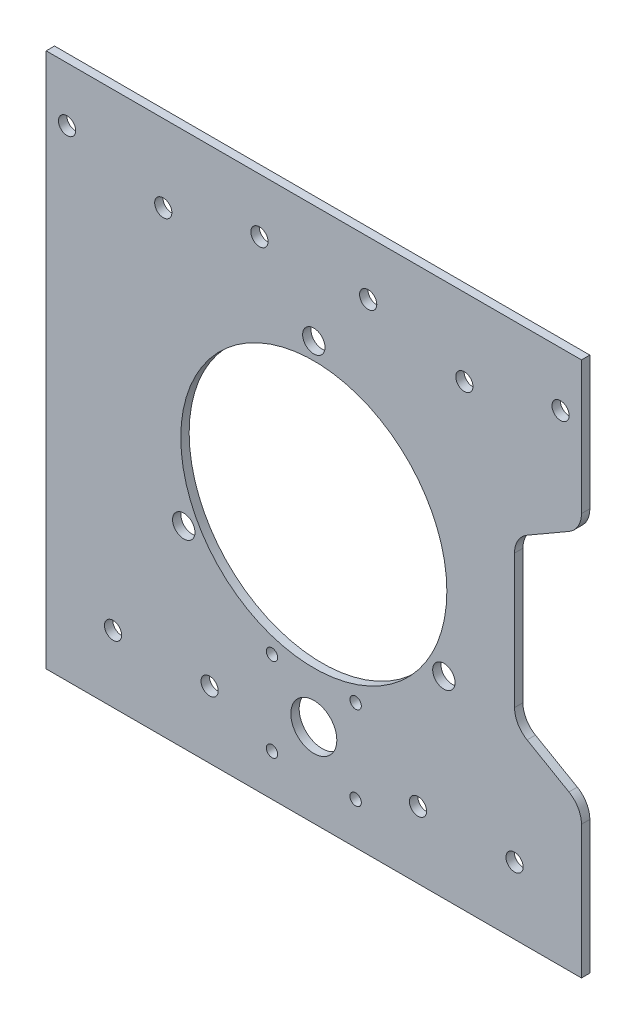
SolidWorks part; units mm, degrees
ref_plane "Front Plane" through (0, 0, 0) normal (0, 0, 1) x (1, 0, 0)
ref_plane "Top Plane" through (0, 0, 0) normal (0, 1, 0) x (1, 0, 0)
ref_plane "Right Plane" through (0, 0, 0) normal (1, 0, 0) x (0, 0, -1)
sketch "Sketch1" plane through (0, 0, 0) normal (0, 0, 1) x (1, 0, 0)
  line L1 (-101.6, -101.6) -> (101.6, -101.6)
  line L2 (-101.6, -101.6) -> (-101.6, 101.6)
  line L3 (-101.6, 101.6) -> (101.6, 101.6)
  line L4 (101.6, -101.6) -> (101.6, 101.6)
  line L5 (-101.6, -101.6) -> (101.6, 101.6) construction
  line L6 (-101.6, 101.6) -> (101.6, -101.6) construction
  point P0 (0, 0)
  dimension "D1" = 203.2
  dimension "D2" = 203.2
extrude "Boss-Extrude1" add sketch "Sketch1" against normal blind 3.175
sketch "Sketch4" plane through (0, 0, 0) normal (1, 0, 0) x (0, 0, -1)
  line L0 (0, 101.6) -> (0, -101.6) construction
  line L1 (0, 63.5) -> (-1.9844, 63.5)
  line L2 (0, 63.5) -> (0, 101.6)
  line L3 (0, 101.6) -> (-0.4801, 103.5254) construction
  line L4 (-1.9844, 63.5) -> (-1.9844, 101.6)
  line L5 (36.9683, 110.8172) -> (0, 101.6)
  line L6 (36.9683, 110.8172) -> (36.4882, 112.7427)
  line L7 (0, 101.6) -> (-1.9844, 101.6) construction
  line L8 (36.4882, 112.7427) -> (-0.4801, 103.5254)
  arc A0 (-0.4801, 103.5254) -> (-1.9844, 101.6) centre (-5.5035, 105.8998) ccw
  circle A1 centre (-5.5035, 105.8998) radius 3.7507
  dimension "D4" = 5.5562
  dimension "D1" = 1.9844
  dimension "D2" = 104
  dimension "D3" = 38.1
  dimension "D6" = 38.1
extrude "Boss-Extrude2" [suppressed] add sketch "Sketch4" along normal mid plane 203.2 separate body
sketch "Sketch5" [suppressed] plane through (0, 0, 1.9844) normal (0, 0, 1) x (1, 0, 0)
  line L0 (101.6, 63.5) -> (-101.6, 63.5) construction
  line L1 (-12.7, 63.5) -> (12.7, 63.5)
  line L2 (-12.7, 63.5) -> (-12.7, 116.2378)
  line L3 (-12.7, 116.2378) -> (12.7, 116.2378)
  line L4 (12.7, 63.5) -> (12.7, 116.2378)
  line L5 (-101.6, 101.6) -> (-101.6, 63.5) construction
  line L6 (101.6, 101.6) -> (101.6, 63.5) construction
  line L7 (-93.6625, 80.9625) -> (-101.6, 80.9625) construction
  line L8 (-93.6625, 80.9625) -> (-20.6375, 80.9625) construction
  line L9 (101.6, 101.6) -> (-101.6, 101.6) construction
  line L11 (0, 101.6) -> (0, 63.5) construction
  line L12 (-20.6375, 80.9625) -> (-12.7, 80.9625) construction
  line L13 (-57.15, 80.9625) -> (-57.15, 72.2313) construction
  line L14 (-57.15, 72.2313) -> (-57.15, 63.5) construction
  circle A0 centre (-93.6625, 80.9625) radius 4.3656
  circle A1 centre (-20.6375, 80.9625) radius 4.3656
  circle A2 centre (20.6375, 80.9625) radius 4.3656
  circle A3 centre (93.6625, 80.9625) radius 4.3656
  circle A4 centre (-57.15, 72.2313) radius 4.3656
  circle A5 centre (57.15, 72.2312) radius 4.3656
  dimension "D5" = 8.7312
  dimension "D3" = 8.7312
  dimension "D1" = 88.9
  dimension "D2" = 88.9
  dimension "D4" = 17.4625
  dimension "D6" = 7.9375
extrude "Cut-Extrude1" [suppressed] cut sketch "Sketch5" against normal through all both and the other way through all
sketch "Sketch6" [suppressed] plane through (0, 97.5792, 24.3292) normal (0, 0.9703, 0.2419) x (1, 0, 0)
  line L0 (101.6, 62.6793) -> (12.7, 62.6793) construction
  line L1 (12.7, 62.6793) -> (12.7, 24.5793) construction
  line L2 (-12.7, 24.5793) -> (-12.7, 62.6793) construction
  line B0 (93.6625, 45.2168) -> (101.6, 45.2168) construction
  line B1 (93.6625, 45.2168) -> (20.6375, 45.2168) construction
  line B2 (20.6375, 45.2168) -> (12.7, 45.2168) construction
  line B3 (57.15, 45.2168) -> (57.15, 53.948) construction
  line B4 (57.15, 53.948) -> (57.15, 62.6793) construction
  circle B5 centre (93.6625, 45.2168) radius 4.3656
  circle B6 centre (20.6375, 45.2168) radius 4.3656
  circle B7 centre (57.15, 53.948) radius 4.3656
  circle B8 centre (-20.6375, 43.6293) radius 4.3656
  circle B9 centre (-93.6625, 43.6293) radius 4.3656
  circle B10 centre (-57.15, 52.3605) radius 4.3656
sketch_block_instance "Block2-1"
sketch_block "Block2" parameters "D1"=8.7312
sketch_block_instance "Block2-2"
extrude "Cut-Extrude2" [suppressed] cut sketch "Sketch6" against normal through all
sketch "Sketch8" plane through (0, 0, 0) normal (0, 0, 1) x (1, 0, 0)
  line L0 (0, 0) -> (0, 57) construction
  line L1 (-49.3634, -28.5) -> (0, 0) construction
  line L2 (49.3634, -28.5) -> (0, 0) construction
  circle A0 centre (0, 0) radius 50.5
  circle A1 centre (0, 0) radius 57 construction
  circle A2 centre (0, 57) radius 4.25
  circle A3 centre (-49.3634, -28.5) radius 4.25
  circle A4 centre (49.3634, -28.5) radius 4.25
  dimension "D1" = 101
  dimension "D4" = 114
  dimension "D5" = 8.5
  dimension "D2" = 120
  dimension "D3" = 120
extrude "Cut-Extrude3" cut sketch "Sketch8" against normal through all
sketch "Sketch10" plane through (0, 0, 0) normal (0, 0, 1) x (1, 0, 0)
  line L0 (101.6, -101.6) -> (101.6, -51.0632) construction
  line L1 (101.6, -101.6) -> (101.6, 101.6) construction
  line L2 (96.8375, 42.8143) -> (80.9625, 33.6489)
  line L3 (76.2, 25.4) -> (76.2, -25.4)
  line L4 (80.9625, -33.6489) -> (96.8375, -42.8143)
  line L5 (101.6, 51.0632) -> (101.6, 101.6) construction
  line L6 (101.6, -51.0632) -> (101.6, 51.0632)
  arc A0 (76.2, -25.4) -> (80.9625, -33.6489) centre (85.725, -25.4) ccw
  arc A1 (80.9625, 33.6489) -> (76.2, 25.4) centre (85.725, 25.4) ccw
  arc A2 (101.6, 51.0632) -> (96.8375, 42.8143) centre (92.075, 51.0632) cw
  arc A3 (96.8375, -42.8143) -> (101.6, -51.0632) centre (92.075, -51.0632) cw
  dimension "D1" = 9.525
  dimension "D2" = 50.8
  dimension "D3" = 25.4
  dimension "D4" = 120
  dimension "D5" = 120
extrude "Cut-Extrude4" cut sketch "Sketch10" against normal through all
hole_wizard "1/4 Clearance Hole2" positions "Sketch12" profile "Sketch11" hole size "1/4" standard "ANSI Inch" end condition through all
sketch "Sketch12" plane through (0, 0, 0) normal (0, 0, 1) x (1, 0, 0)
  line L0 (101.6, -76.2) -> (76.2, -76.2) construction
  line L1 (101.6, -101.6) -> (101.6, -51.0632) construction
  line L2 (76.2, -76.2) -> (39.5531, -76.2) construction
  line L3 (39.5531, -76.2) -> (-39.5531, -76.2) construction
  line L4 (-39.5531, -76.2) -> (-76.2, -76.2) construction
  line L5 (-76.2, -76.2) -> (-101.6, -76.2) construction
  line L6 (-101.6, 101.6) -> (-101.6, -101.6) construction
  line L7 (-101.6, -101.6) -> (101.6, -101.6) construction
  point P0 (76.2, -76.2)
  point P2 (39.5531, -76.2)
  point P4 (-39.5531, -76.2)
  point P6 (-76.2, -76.2)
  dimension "D2" = 25.4
sketch "Sketch11" plane through (76.2, -76.2, 0) normal (1, 0, 0) x (0, -1, 0)
  line L0 (0, 0) -> (0, 3.175)
  line L1 (0, 3.175) -> (3.2639, 3.175)
  line L2 (3.2639, 3.175) -> (3.2639, 0)
  line L5 (3.2639, 0) -> (0, 0)
  line L11 (0, -6.35) -> (0, 107.95) construction
  dimension "Thru Hole Dia." = 6.5278
  dimension "Thru Hole Depth" = 3.175
hole_wizard "1/4 Clearance Hole1" positions "Sketch16" profile "Sketch15" hole size "1/4" standard "ANSI Inch" end condition through all
sketch "Sketch16" plane through (0, 0, 0) normal (0, 0, 1) x (1, 0, 0)
  point P0 (-93.6625, 80.9625)
  point P3 (-57.15, 72.2313)
  point P6 (-20.6375, 80.9625)
  point P9 (20.6375, 80.9625)
  point P12 (57.15, 72.2312)
  point P15 (93.6625, 80.9625)
sketch "Sketch15" plane through (-93.6625, 80.9625, 0) normal (1, 0, 0) x (0, -1, 0)
  line L0 (0, 0) -> (0, 3.175)
  line L1 (0, 3.175) -> (3.2639, 3.175)
  line L2 (3.2639, 3.175) -> (3.2639, 0)
  line L5 (3.2639, 0) -> (0, 0)
  line L11 (0, -6.35) -> (0, 107.95) construction
  dimension "Thru Hole Dia." = 6.5278
  dimension "Thru Hole Depth" = 3.175
hole_wizard "#8 Clearance Hole2" positions "Sketch18" profile "Sketch17" hole size "#8" standard "ANSI Inch" end condition through all
sketch "Sketch18" plane through (0, 0, 0) normal (0, 0, 1) x (1, 0, 0)
  line L2 (0, -85.7425) -> (0, -101.6) construction
  line L3 (-101.6, -101.6) -> (101.6, -101.6) construction
  line L4 (-15.875, -53.9575) -> (15.875, -53.9575) construction
  line L5 (15.875, -53.9575) -> (15.875, -85.7425) construction
  line L6 (15.875, -85.7425) -> (-15.875, -85.7425) construction
  line L7 (-15.875, -85.7425) -> (-15.875, -53.9575) construction
  line L9 (-15.875, -69.85) -> (15.875, -69.85) construction
  point P0 (-15.875, -53.9575)
  point P2 (15.875, -53.9575)
  point P4 (-15.875, -85.7425)
  point P6 (15.875, -85.7425)
  dimension "D1" = 31.75
  dimension "D2" = 31.785
  dimension "D3" = 69.85
sketch "Sketch17" plane through (-15.875, -53.9575, 0) normal (1, 0, 0) x (0, -1, 0)
  line L0 (0, 0) -> (0, 3.175)
  line L1 (0, 3.175) -> (2.1526, 3.175)
  line L2 (2.1526, 3.175) -> (2.1526, 0)
  line L5 (2.1526, 0) -> (0, 0)
  line L11 (0, -6.35) -> (0, 107.95) construction
  dimension "Thru Hole Dia." = 4.3053
  dimension "Thru Hole Depth" = 3.175
sketch "Sketch19" plane through (0, 0, 0) normal (0, 0, 1) x (1, 0, 0)
  line L0 (-15.875, -85.7425) -> (15.875, -53.9575) construction
  circle A0 centre (0, -69.85) radius 8.7313
  dimension "D1" = 17.4625
extrude "Cut-Extrude5" cut sketch "Sketch19" against normal through all
